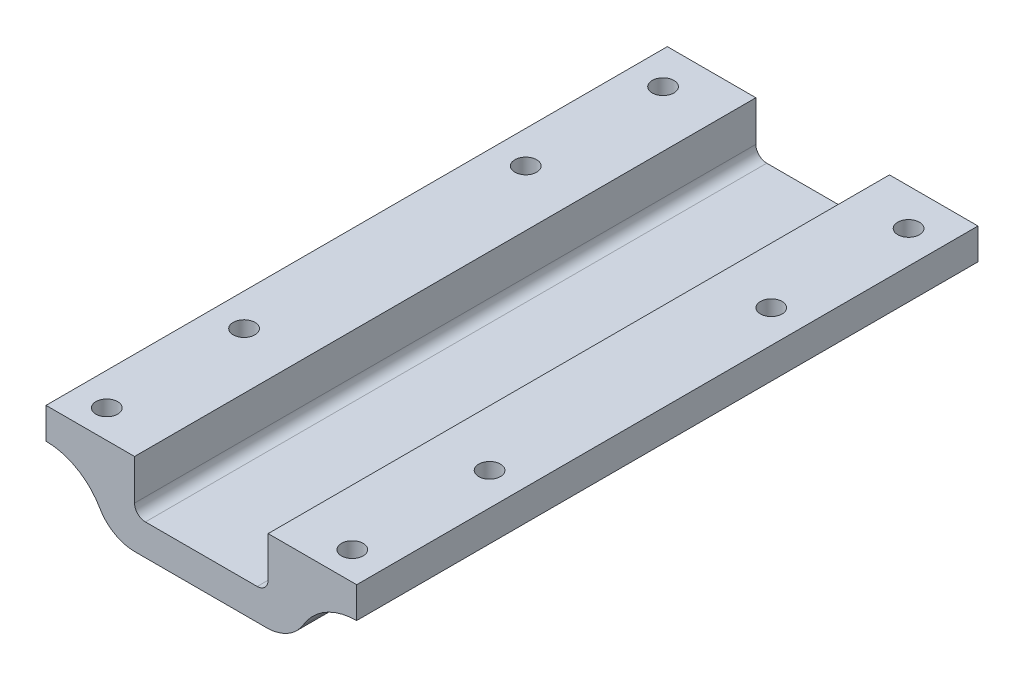
SolidWorks part; units mm, degrees
ref_plane "Front Plane" through (0, 0, 0) normal (0, 0, 1) x (1, 0, 0)
ref_plane "Top Plane" through (0, 0, 0) normal (0, 1, 0) x (1, 0, 0)
ref_plane "Right Plane" through (0, 0, 0) normal (1, 0, 0) x (0, 0, -1)
sketch "Sketch1" plane through (0, 0, 0) normal (0, 0, 1) x (1, 0, 0)
  line L0 (15, 13.2239) -> (35, 13.2239) construction
  line L1 (50, 10.2246) -> (50, 5.2246)
  line L2 (35.75, 10.2246) -> (50, 10.2246)
  line L3 (35.75, 3.7246) -> (35.75, 10.2246)
  line L4 (15, 22.2239) -> (15, 4.2239)
  line L5 (16, 3.2239) -> (34, 3.2239)
  line L6 (35, 4.2239) -> (35, 22.2239)
  line L7 (34, 23.2239) -> (16, 23.2239)
  line L8 (15, 22.2239) -> (15, 4.2239) construction
  line L9 (16, 3.2239) -> (34, 3.2239) construction
  line L10 (35, 4.2239) -> (35, 22.2239) construction
  line L11 (34, 23.2239) -> (16, 23.2239) construction
  line L12 (16, 1.9746) -> (34, 1.9746)
  line L13 (14.25, 10.2246) -> (14.25, 3.7246)
  line L14 (0, 10.2246) -> (14.25, 10.2246)
  line L15 (0, 5.2246) -> (0, 10.2246)
  line L16 (37.0096, 28.7233) -> (12.9904, 28.7233)
  line L17 (0, 21.2233) -> (0, 16.2233)
  line L18 (0, 16.2233) -> (14.25, 16.2233)
  line L19 (14.25, 16.2233) -> (14.25, 22.7233)
  line L20 (16, 24.4733) -> (34, 24.4733)
  line L21 (35.75, 22.7233) -> (35.75, 16.2233)
  line L22 (35.75, 16.2233) -> (50, 16.2233)
  line L23 (50, 16.2233) -> (50, 21.2233)
  line L24 (37.0096, 28.7233) -> (12.9904, 28.7233) construction
  line L25 (0, 21.2233) -> (0, 16.2233) construction
  line L26 (0, 16.2233) -> (14.25, 16.2233) construction
  line L27 (14.25, 16.2233) -> (14.25, 22.7233) construction
  line L28 (16, 24.4733) -> (34, 24.4733) construction
  line L29 (35.75, 22.7233) -> (35.75, 16.2233) construction
  line L30 (35.75, 16.2233) -> (50, 16.2233) construction
  line L31 (50, 16.2233) -> (50, 21.2233) construction
  line L33 (14.2894, -3.0254) -> (35.7106, -3.0254)
  arc A1 (41.3397, 0.2246) -> (50, 5.2246) centre (50, -4.7754) cw
  arc A2 (35.75, 3.7246) -> (34, 1.9746) centre (34, 3.7246) cw
  arc A3 (16, 1.9746) -> (14.25, 3.7246) centre (16, 3.7246) cw
  arc A4 (16, 23.2239) -> (15, 22.2239) centre (16, 22.2239) ccw
  arc A5 (15, 4.2239) -> (16, 3.2239) centre (16, 4.2239) ccw
  arc A6 (34, 3.2239) -> (35, 4.2239) centre (34, 4.2239) ccw
  arc A7 (35, 22.2239) -> (34, 23.2239) centre (34, 22.2239) ccw
  arc A8 (16, 23.2239) -> (15, 22.2239) centre (16, 22.2239) ccw construction
  arc A9 (15, 4.2239) -> (16, 3.2239) centre (16, 4.2239) ccw construction
  arc A10 (34, 3.2239) -> (35, 4.2239) centre (34, 4.2239) ccw construction
  arc A11 (35, 22.2239) -> (34, 23.2239) centre (34, 22.2239) ccw construction
  arc A12 (0, 5.2246) -> (8.6603, 0.2246) centre (0, -4.7754) cw
  arc A14 (12.9904, 28.7233) -> (8.6603, 26.2233) centre (12.9904, 23.7233) ccw
  arc A15 (0, 21.2233) -> (8.6603, 26.2233) centre (0, 31.2233) ccw
  arc A16 (16, 24.4733) -> (14.25, 22.7233) centre (16, 22.7233) ccw
  arc A17 (35.75, 22.7233) -> (34, 24.4733) centre (34, 22.7233) ccw
  arc A18 (41.3397, 26.2233) -> (50, 21.2233) centre (50, 31.2233) ccw
  arc A19 (41.3397, 26.2233) -> (37.0096, 28.7233) centre (37.0096, 23.7233) ccw
  arc A20 (12.9904, 28.7233) -> (8.6603, 26.2233) centre (12.9904, 23.7233) ccw construction
  arc A21 (0, 21.2233) -> (8.6603, 26.2233) centre (0, 31.2233) ccw construction
  arc A22 (16, 24.4733) -> (14.25, 22.7233) centre (16, 22.7233) ccw construction
  arc A23 (35.75, 22.7233) -> (34, 24.4733) centre (34, 22.7233) ccw construction
  arc A24 (41.3397, 26.2233) -> (50, 21.2233) centre (50, 31.2233) ccw construction
  arc A25 (41.3397, 26.2233) -> (37.0096, 28.7233) centre (37.0096, 23.7233) ccw construction
  arc A26 (8.6603, 0.2246) -> (14.2894, -3.0254) centre (14.2894, 3.4746) ccw
  arc A27 (35.7106, -3.0254) -> (41.3397, 0.2246) centre (35.4411, 3.9414) ccw
  point P52 (25, -3.0254)
  point P53 (25, 1.9746)
  point P57 (14.25, -3.0254)
  point P58 (14.2894, -3.0254)
  point P59 (41.3397, 0.2246)
  dimension "D3" = 5
  dimension "D1" = 0
  dimension "D2" = 0
extrude "Boss-Extrude1" add sketch "Sketch1" against normal up to surface (100 mm away)
sketch "Sketch2" plane through (0, -3.0254, 0) normal (0, -1, 0) x (1, 0, 0)
  circle A0 centre (44.7568, -26.6349) radius 1.75 construction
  circle A1 centre (44.7568, -4.5371) radius 1.75 construction
  circle A2 centre (44.7568, -71.973) radius 1.75 construction
  circle A3 centre (44.7568, -94.0708) radius 1.75 construction
  circle A4 centre (5.2432, -71.973) radius 1.75 construction
  circle A5 centre (5.2432, -94.0708) radius 1.75 construction
  circle A6 centre (5.2432, -26.6349) radius 1.75 construction
  circle A7 centre (5.2432, -4.5371) radius 1.75 construction
  circle A8 centre (44.7568, -26.6349) radius 1.75
  circle A9 centre (44.7568, -4.5371) radius 1.75
  circle A10 centre (44.7568, -71.973) radius 1.75
  circle A11 centre (44.7568, -94.0708) radius 1.75
  circle A12 centre (5.2432, -71.973) radius 1.75
  circle A13 centre (5.2432, -94.0708) radius 1.75
  circle A14 centre (5.2432, -26.6349) radius 1.75
  circle A15 centre (5.2432, -4.5371) radius 1.75
extrude "Cut-Extrude1" cut sketch "Sketch2" against normal through all
sketch "Sketch3" plane through (0, -3.0254, 0) normal (0, -1, 0) x (1, 0, 0)
  line L0 (25, 0) -> (25, -100) construction
  line L1 (8.2432, -2.8051) -> (5.2432, -1.073)
  line L2 (5.2432, -1.073) -> (2.2432, -2.8051)
  line L3 (2.2432, -2.8051) -> (2.2432, -6.2692)
  line L4 (2.2432, -6.2692) -> (5.2432, -8.0012)
  line L5 (5.2432, -8.0012) -> (8.2432, -6.2692)
  line L6 (8.2432, -6.2692) -> (8.2432, -2.8051)
  line L7 (5.264, -23.1709) -> (2.2537, -24.8848)
  line L8 (2.2537, -24.8848) -> (2.2328, -28.3489)
  line L9 (2.2328, -28.3489) -> (5.2223, -30.0989)
  line L10 (5.2223, -30.0989) -> (8.2327, -28.385)
  line L11 (8.2327, -28.385) -> (8.2535, -24.9209)
  line L12 (8.2535, -24.9209) -> (5.264, -23.1709)
  line L13 (14.2894, 0) -> (35.7106, 0) construction
  line L14 (35.7106, -100) -> (14.2894, -100) construction
  line L15 (25, -100) -> (0, -50) construction
  line L16 (0, -100) -> (0, 0) construction
  line L17 (0, -50) -> (50, -50) construction
  line L18 (50, -100) -> (50, 0) construction
  line L19 (41.7465, -24.9209) -> (44.736, -23.1709)
  line L20 (41.7673, -28.385) -> (41.7465, -24.9209)
  line L21 (44.7777, -30.0989) -> (41.7673, -28.385)
  line L22 (47.7672, -28.3489) -> (44.7777, -30.0989)
  line L23 (47.7463, -24.8848) -> (47.7672, -28.3489)
  line L24 (44.736, -23.1709) -> (47.7463, -24.8848)
  line L25 (41.7568, -6.2692) -> (41.7568, -2.8051)
  line L26 (44.7568, -8.0012) -> (41.7568, -6.2692)
  line L27 (47.7568, -6.2692) -> (44.7568, -8.0012)
  line L28 (47.7568, -2.8051) -> (47.7568, -6.2692)
  line L29 (44.7568, -1.073) -> (47.7568, -2.8051)
  line L30 (41.7568, -2.8051) -> (44.7568, -1.073)
  line L31 (41.7568, -92.3387) -> (44.7568, -90.6067)
  line L32 (5.2516, -68.5089) -> (2.2474, -70.2336)
  line L33 (2.2474, -70.2336) -> (2.239, -73.6977)
  line L34 (2.239, -73.6977) -> (5.2347, -75.4371)
  line L35 (5.2347, -75.4371) -> (8.2389, -73.7123)
  line L36 (8.2389, -73.7123) -> (8.2474, -70.2482)
  line L37 (8.2474, -70.2482) -> (5.2516, -68.5089)
  line L38 (5.2432, -90.6067) -> (2.2432, -92.3387)
  line L39 (2.2432, -92.3387) -> (2.2432, -95.8028)
  line L40 (2.2432, -95.8028) -> (5.2432, -97.5349)
  line L41 (5.2432, -97.5349) -> (8.2432, -95.8028)
  line L42 (8.2432, -95.8028) -> (8.2432, -92.3387)
  line L43 (8.2432, -92.3387) -> (5.2432, -90.6067)
  line L44 (41.7568, -95.8028) -> (41.7568, -92.3387)
  line L45 (44.7568, -97.5349) -> (41.7568, -95.8028)
  line L46 (47.7568, -95.8028) -> (44.7568, -97.5349)
  line L47 (47.7568, -92.3387) -> (47.7568, -95.8028)
  line L48 (44.7568, -90.6067) -> (47.7568, -92.3387)
  line L49 (41.7526, -70.2482) -> (44.7484, -68.5089)
  line L50 (41.7611, -73.7123) -> (41.7526, -70.2482)
  line L51 (44.7653, -75.4371) -> (41.7611, -73.7123)
  line L52 (47.761, -73.6977) -> (44.7653, -75.4371)
  line L53 (47.7526, -70.2336) -> (47.761, -73.6977)
  line L54 (44.7484, -68.5089) -> (47.7526, -70.2336)
  circle A0 centre (5.2432, -4.5371) radius 3 construction
  circle A1 centre (5.2432, -26.6349) radius 3 construction
  circle A2 centre (44.7568, -26.6349) radius 3 construction
  circle A3 centre (44.7568, -4.5371) radius 3 construction
  circle A4 centre (5.2432, -71.973) radius 3 construction
  circle A5 centre (5.2432, -94.0708) radius 3 construction
  circle A6 centre (44.7568, -94.0708) radius 3 construction
  circle A7 centre (44.7568, -71.973) radius 3 construction
  dimension "D1" = 6
extrude "Cut-Extrude2" cut sketch "Sketch3" against normal up to vertex (8.25 mm away)
